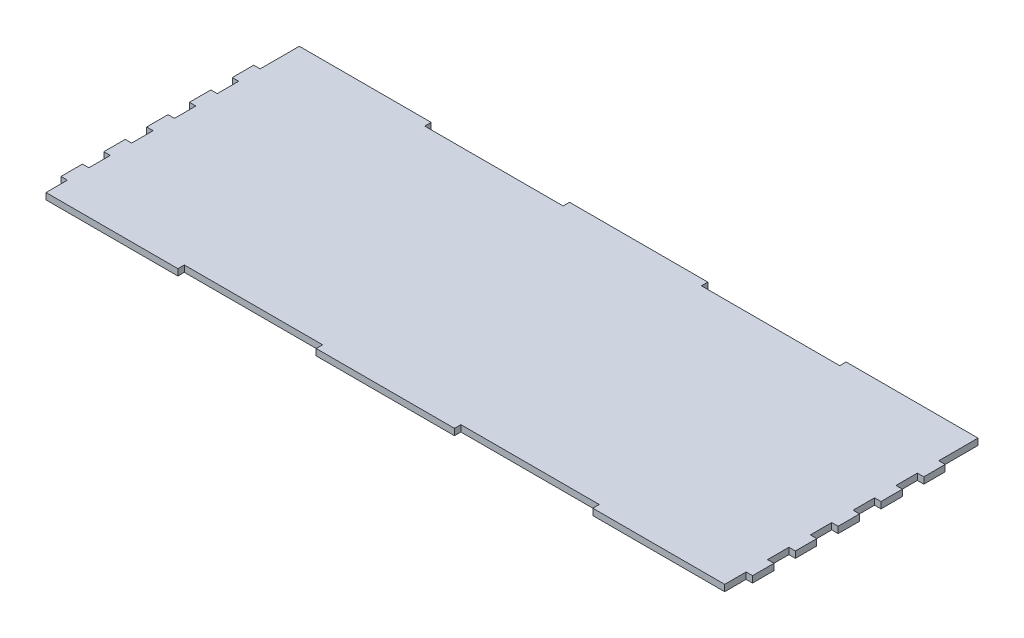
SolidWorks part; units mm, degrees
ref_plane "Front Plane" through (0, 0, 0) normal (0, 0, 1) x (1, 0, 0)
ref_plane "Top Plane" through (0, 0, 0) normal (0, 1, 0) x (1, 0, 0)
ref_plane "Right Plane" through (0, 0, 0) normal (1, 0, 0) x (0, 0, -1)
sketch "Sketch1" plane through (0, 0, 0) normal (0, 1, 0) x (1, 0, 0)
  line L0 (3, 0) -> (3, 10)
  line L1 (320, 118.32) -> (320, 100)
  line L2 (3, 10) -> (0, 10)
  line L3 (320, 100) -> (323, 100)
  line L4 (323, 100) -> (323, 90)
  line L5 (0, 10) -> (0, 20)
  line L6 (0, 20) -> (3, 20)
  line L7 (3, 20) -> (3, 30)
  line L8 (3, 30) -> (0, 30)
  line L9 (0, 30) -> (0, 40)
  line L10 (0, 40) -> (3, 40)
  line L11 (3, 40) -> (3, 50)
  line L12 (3, 50) -> (0, 50)
  line L13 (0, 50) -> (0, 60)
  line L14 (0, 60) -> (3, 60)
  line L15 (3, 60) -> (3, 70)
  line L16 (3, 70) -> (0, 70)
  line L17 (0, 70) -> (0, 80)
  line L18 (0, 80) -> (3, 80)
  line L19 (3, 80) -> (3, 90)
  line L20 (3, 90) -> (0, 90)
  line L21 (0, 90) -> (0, 100)
  line L22 (0, 100) -> (3, 100)
  line L23 (3, 100) -> (3, 118.32)
  line L24 (323, 90) -> (320, 90)
  line L25 (320, 90) -> (320, 80)
  line L26 (320, 80) -> (323, 80)
  line L27 (323, 80) -> (323, 70)
  line L28 (323, 70) -> (320, 70)
  line L29 (320, 70) -> (320, 60)
  line L30 (320, 60) -> (323, 60)
  line L31 (323, 60) -> (323, 50)
  line L32 (323, 50) -> (320, 50)
  line L33 (320, 50) -> (320, 40)
  line L34 (320, 40) -> (323, 40)
  line L35 (323, 40) -> (323, 30)
  line L36 (323, 30) -> (320, 30)
  line L37 (320, 30) -> (320, 20)
  line L38 (320, 20) -> (323, 20)
  line L39 (323, 20) -> (323, 10)
  line L40 (323, 10) -> (320, 10)
  line L41 (320, 10) -> (320, 0)
  line L42 (3, 0) -> (64.6, 0)
  line L43 (3, 118.32) -> (64.6, 118.32)
  line L44 (64.6, 118.32) -> (64.6, 115.32)
  line L45 (64.6, 115.32) -> (129.2, 115.32)
  line L46 (129.2, 115.32) -> (129.2, 118.32)
  line L47 (129.2, 118.32) -> (193.8, 118.32)
  line L48 (193.8, 118.32) -> (193.8, 115.32)
  line L49 (193.8, 115.32) -> (258.4, 115.32)
  line L50 (258.4, 115.32) -> (258.4, 118.32)
  line L51 (258.4, 118.32) -> (320, 118.32)
  line L52 (64.6, 0) -> (64.6, 3)
  line L53 (64.6, 3) -> (129.2, 3)
  line L54 (129.2, 3) -> (129.2, 0)
  line L55 (129.2, 0) -> (193.8, 0)
  line L56 (193.8, 0) -> (193.8, 3)
  line L57 (193.8, 3) -> (258.4, 3)
  line L58 (258.4, 3) -> (258.4, 0)
  line L59 (258.4, 0) -> (320, 0)
  dimension "D2" = 3
  dimension "D3" = 3
  dimension "D4" = 3
  dimension "D5" = 3
  dimension "D6" = 3
  dimension "D7" = 10
  dimension "D8" = 10
  dimension "D9" = 10
  dimension "D10" = 10
  dimension "D11" = 10
  dimension "D12" = 10
  dimension "D13" = 10
  dimension "D14" = 10
  dimension "D15" = 10
  dimension "D16" = 10
  dimension "D17" = 317
  dimension "D18" = 317
  dimension "D19" = 3
  dimension "D20" = 61.6
  dimension "D21" = 61.6
  dimension "D22" = 64.6
  dimension "D23" = 64.6
  dimension "D24" = 3
extrude "Boss-Extrude4" add sketch "Sketch1" along normal blind 3
